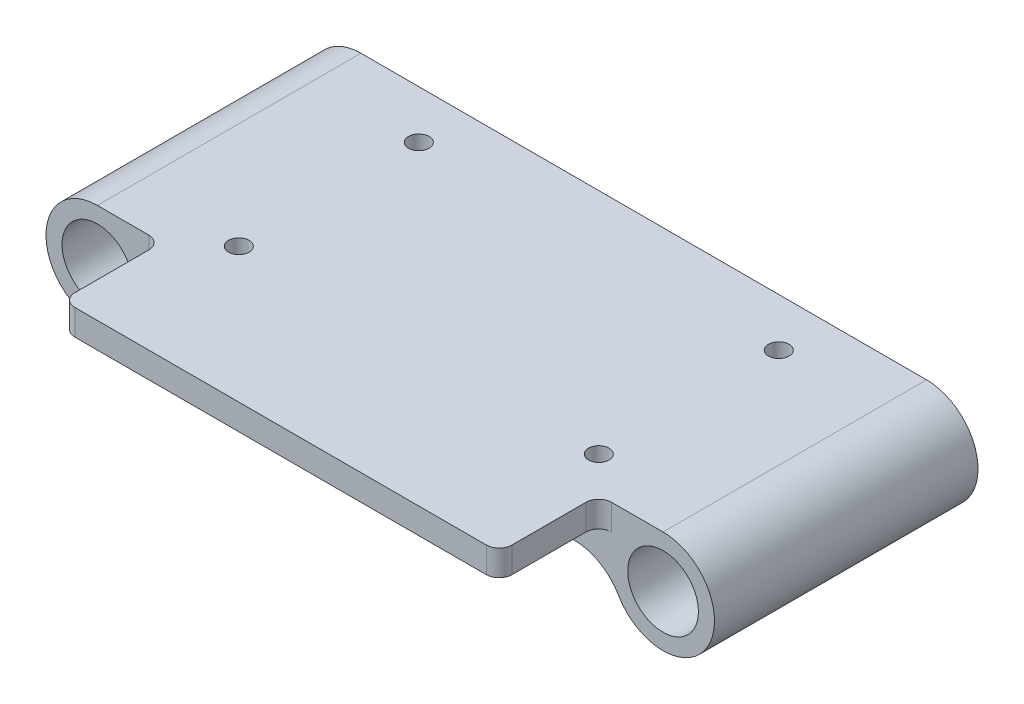
SolidWorks part; units mm, degrees
material "ABS"
ref_plane "Front Plane" through (0, 0, 0) normal (0, 0, 1) x (1, 0, 0)
ref_plane "Top Plane" through (0, 0, 0) normal (0, 1, 0) x (1, 0, 0)
ref_plane "Right Plane" through (0, 0, 0) normal (1, 0, 0) x (0, 0, -1)
sketch "Sketch1" plane through (0, 0, 0) normal (0, 0, 1) x (1, 0, 0)
  line L0 (22, 0) -> (-22, 0)
  line L1 (-22, 4) -> (22, 4)
  line L2 (0, 4) -> (0, 0) construction
  circle A2 centre (-22, 0) radius 4
  circle A3 centre (22, 0) radius 4
  dimension "D1" = 8
  dimension "D2" = 22
extrude "Boss-Extrude1" add sketch "Sketch1" along normal mid plane 20.5
ref_plane "Plane1" through (0, 2, 0) normal (0, 1, 0) x (1, 0, 0)
fillet "Fillet1" radius 4 2 edges at (18, 0, 0) (-18, 0, 0)
sketch "Sketch7" plane through (0, 2, 0) normal (0, -1, 0) x (1, 0, 0)
  line L1 (-17, 18) -> (17, 18)
  line L2 (15.0718, 10.25) -> (-15.0718, 10.25) construction
  line L5 (0, -10.25) -> (0, 0) construction
  line L6 (15.0718, -10.25) -> (-15.0718, -10.25) construction
  line L7 (15.0718, -10.25) -> (-15.0718, -10.25)
  line L10 (15.0718, 10.25) -> (-15.0718, 10.25)
  line L11 (-15.0718, 10.25) -> (-17, 10.25)
  line L12 (-15.0718, 10.25) -> (-18.5359, 10.25) construction
  line L13 (-17, 10.25) -> (-17, 18)
  line L14 (15.0718, 10.25) -> (17, 10.25)
  line L15 (17, 10.25) -> (17, 18)
  point P18 (0, 18)
  dimension "D1" = 90
  dimension "D2" = 17
  dimension "D3" = 7.75
extrude "Boss-Extrude2" add sketch "Sketch7" against normal up to surface (2 mm away) contours L15 L14 L10 L11 L13 L1 up to face at (0, 4, 0)
hole_wizard "M5 Clearance Hole1" positions "Sketch2" profile "Sketch3" hole size "M5" standard "ANSI Metric" end condition through all
sketch "Sketch2" plane through (0, 0, 10.25) normal (0, 0, 1) x (1, 0, 0)
  point P0 (-22, 0)
  point P3 (22, 0)
sketch "Sketch3" plane through (-22, 0, 10.25) normal (1, 0, 0) x (0, -1, 0)
  line L0 (0, 0) -> (0, 20.5)
  line L1 (0, 20.5) -> (2.75, 20.5)
  line L2 (2.75, 20.5) -> (2.75, 0)
  line L5 (2.75, 0) -> (0, 0)
  line L11 (0, -6.35) -> (0, 107.95) construction
  dimension "Thru Hole Dia." = 5.5
  dimension "Thru Hole Depth" = 20.5
hole_wizard "M2x0.4 Tapped Hole1" positions "Sketch4" profile "Sketch5" tap size "M2x0.4" standard "ANSI Metric" end condition through all
sketch "Sketch4" plane through (0, 4, 0) normal (0, 1, 0) x (1, 0, 0)
  point P0 (14.25, 6.5)
  point P3 (14.25, -7.5)
  point P6 (-13.75, -7.5)
  point P9 (-13.75, 6.5)
sketch "Sketch5" plane through (14.25, 4, -6.5) normal (1, 0, 0) x (0, 0, 1)
  line L0 (0, 0) -> (0, 8)
  line L1 (0, 8) -> (0.8, 8)
  line L2 (0.8, 8) -> (0.8, 0)
  line L5 (0.8, 0) -> (0, 0)
  line L11 (0, -6.35) -> (0, 107.95) construction
  dimension "Thru Tap Drill Dia." = 1.6
  dimension "Thru Tap Drill Depth" = 8
fillet "Fillet2" radius 1 4 edges at (-17, 3, 18) (17, 3, 18) (17, 3, 10.25) (-17, 3, 10.25)
